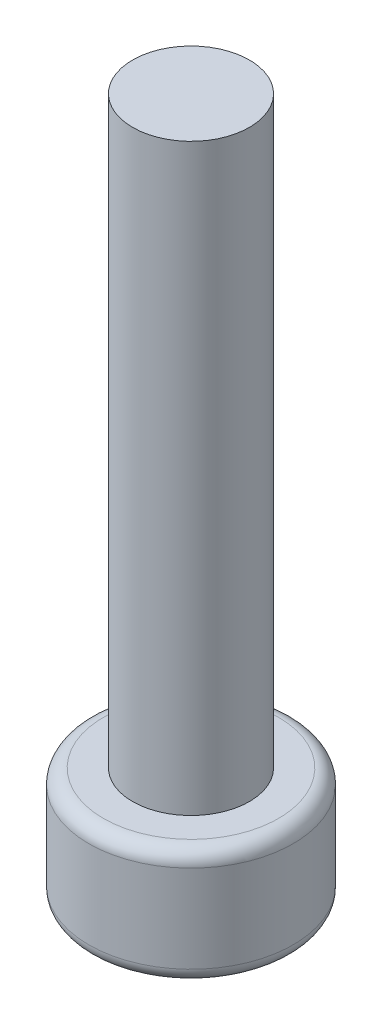
SolidWorks part; units mm, degrees
ref_plane "前视基准面" through (0, 0, 0) normal (0, 0, 1) x (1, 0, 0)
ref_plane "上视基准面" through (0, 0, 0) normal (0, 1, 0) x (1, 0, 0)
ref_plane "右视基准面" through (0, 0, 0) normal (1, 0, 0) x (0, 0, -1)
sketch "草图1" plane through (0, 0, 0) normal (0, 1, 0) x (1, 0, 0)
  circle A0 centre (0, 0) radius 3.5
  dimension "D1" = 7
extrude "凸台-拉伸1" add sketch "草图1" along normal blind 4
sketch "草图2" plane through (0, 4, 0) normal (0, 1, 0) x (1, 0, 0)
  circle A0 centre (0, 0) radius 2
  dimension "D1" = 4
extrude "凸台-拉伸2" add sketch "草图2" along normal blind 20
cosmetic thread "装饰螺纹线1" parameters "D2"=3
sketch "草图3" plane through (0, 0, 0) normal (0, -1, 0) x (1, 0, 0)
  line L0 (-2.8141, 0) -> (3.2226, 0) construction
  line L2 (1.5, 0) -> (0.75, 1.299)
  line L3 (0.75, 1.299) -> (-0.75, 1.299)
  line L4 (-0.75, 1.299) -> (-1.5, 0)
  line L5 (-1.5, 0) -> (-0.75, -1.299)
  line L6 (-0.75, -1.299) -> (0.75, -1.299)
  line L7 (0.75, -1.299) -> (1.5, 0)
  circle A0 centre (0, 0) radius 1.299 construction
  dimension "D1" = 3
extrude "切除-拉伸1" cut sketch "草图3" against normal blind 2
fillet "圆角1" radius 0.5 2 edges at (0, 0, 3.5) (0, 4, 3.5)
